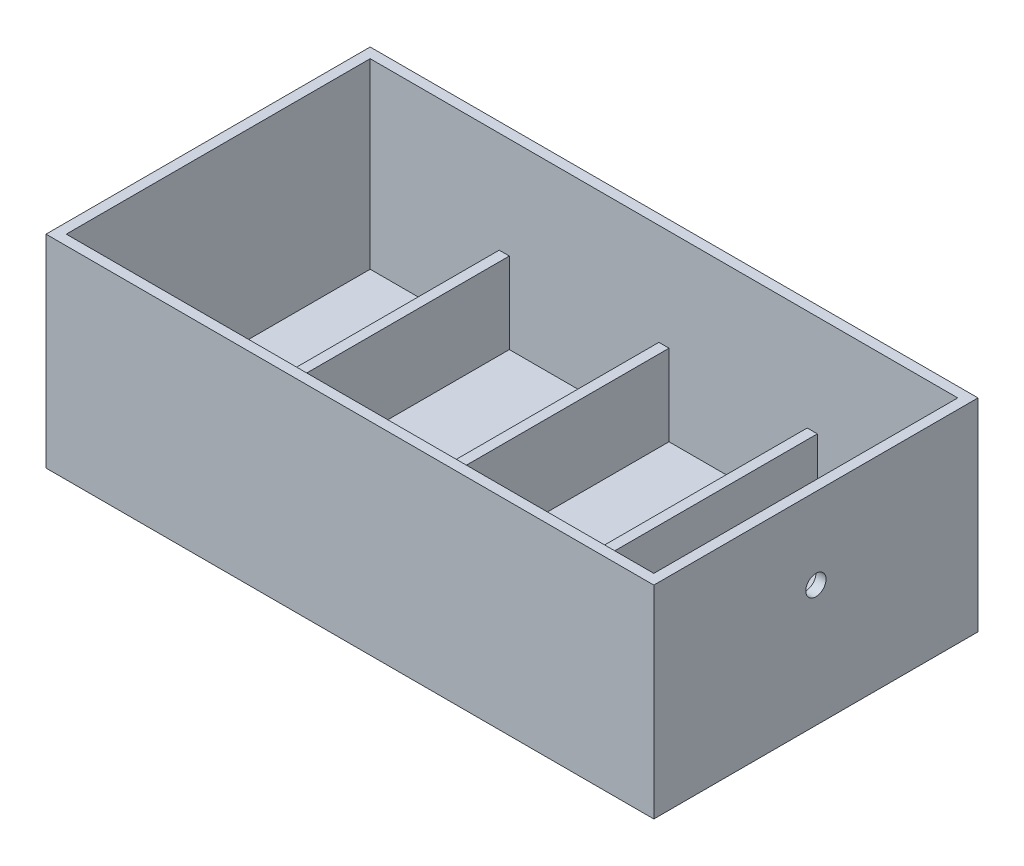
SolidWorks part; units mm, degrees
ref_plane "Front Plane" through (0, 0, 0) normal (0, 0, 1) x (1, 0, 0)
ref_plane "Top Plane" through (0, 0, 0) normal (0, 1, 0) x (1, 0, 0)
ref_plane "Right Plane" through (0, 0, 0) normal (1, 0, 0) x (0, 0, -1)
sketch "Sketch1" plane through (0, 0, 0) normal (0, 1, 0) x (1, 0, 0)
  line L1 (75, -40) -> (-75, -40)
  line L2 (75, -40) -> (75, 40)
  line L3 (75, 40) -> (-75, 40)
  line L4 (-75, -40) -> (-75, 40)
  line L5 (75, -40) -> (-75, 40) construction
  line L6 (75, 40) -> (-75, -40) construction
  point P0 (0, 0)
  dimension "D1" = 150
  dimension "D2" = 80
extrude "Boss-Extrude1" add sketch "Sketch1" along normal blind 50
sketch "Sketch2" plane through (0, 50, 0) normal (0, 1, 0) x (1, 0, 0)
  line L1 (72.5, -37.5) -> (-72.5, -37.5)
  line L2 (72.5, -37.5) -> (72.5, 37.5)
  line L3 (72.5, 37.5) -> (-72.5, 37.5)
  line L4 (-72.5, -37.5) -> (-72.5, 37.5)
  line L5 (72.5, -37.5) -> (-72.5, 37.5) construction
  line L6 (72.5, 37.5) -> (-72.5, -37.5) construction
  point P0 (0, 0)
  dimension "D1" = 145
  dimension "D2" = 75
extrude "Cut-Extrude1" cut sketch "Sketch2" against normal blind 45
sketch "Sketch6" plane through (0, 5, 0) normal (0, 1, 0) x (1, 0, 0)
  line L0 (72.5, 37.5) -> (-72.5, 37.5) construction
  line L1 (1.25, -37.5) -> (-1.25, -37.5)
  line L2 (1.25, -37.5) -> (1.25, 37.5)
  line L3 (1.25, 37.5) -> (-1.25, 37.5)
  line L4 (-1.25, -37.5) -> (-1.25, 37.5)
  line L5 (1.25, -37.5) -> (-1.25, 37.5) construction
  line L6 (1.25, 37.5) -> (-1.25, -37.5) construction
  point P0 (0, 0)
  dimension "D1" = 2.5
sketch "Sketch7" plane through (0, 5, 0) normal (0, 1, 0) x (1, 0, 0)
  line L0 (72.5, 37.5) -> (-72.5, 37.5) construction
  line L1 (-38.1547, -37.5) -> (-40.6547, -37.5)
  line L2 (-38.1547, -37.5) -> (-38.1547, 37.5)
  line L3 (-38.1547, 37.5) -> (-40.6547, 37.5)
  line L4 (-40.6547, -37.5) -> (-40.6547, 37.5)
  line L5 (-38.1547, -37.5) -> (-40.6547, 37.5) construction
  line L6 (-38.1547, 37.5) -> (-40.6547, -37.5) construction
  point P0 (-39.4047, 0)
  dimension "D1" = 2.5
sketch "Sketch10" plane through (0, 5, 0) normal (0, 1, 0) x (1, 0, 0)
  line L0 (72.5, 37.5) -> (-72.5, 37.5) construction
  line L1 (37.8563, -37.5) -> (35.3563, -37.5)
  line L2 (37.8563, -37.5) -> (37.8563, 37.5)
  line L3 (37.8563, 37.5) -> (35.3563, 37.5)
  line L4 (35.3563, -37.5) -> (35.3563, 37.5)
  line L5 (37.8563, -37.5) -> (35.3563, 37.5) construction
  line L6 (37.8563, 37.5) -> (35.3563, -37.5) construction
  point P0 (36.6063, 0)
  dimension "D1" = 2.5
extrude "Boss-Extrude3" add sketch "Sketch6" along normal blind 20
extrude "Boss-Extrude4" add sketch "Sketch7" along normal blind 20
extrude "Boss-Extrude5" add sketch "Sketch10" along normal blind 20
sketch "Sketch12" plane through (75, 0, 0) normal (1, 0, 0) x (0, 0, -1)
  circle A0 centre (0, 30) radius 2.5
extrude "Cut-Extrude8" cut sketch "Sketch12" against normal blind 10
